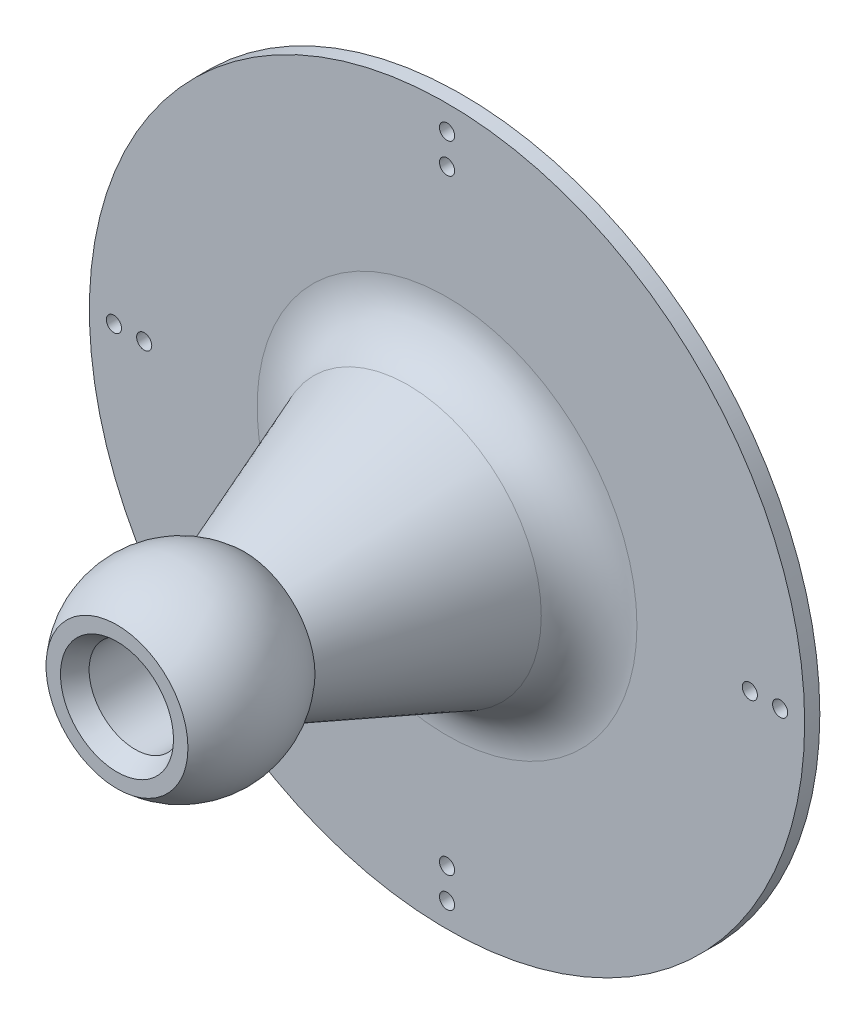
SolidWorks part; units mm, degrees
ref_plane "Front Plane" through (0, 0, 0) normal (0, 0, 1) x (1, 0, 0)
ref_plane "Top Plane" through (0, 0, 0) normal (0, 1, 0) x (1, 0, 0)
ref_plane "Right Plane" through (0, 0, 0) normal (1, 0, 0) x (0, 0, -1)
sketch "Sketch1" plane through (0, 0, 0) normal (0, 1, 0) x (1, 0, 0)
  line L0 (75, 1.2937) -> (0, 1.2937)
  line L1 (0, 1.2937) -> (0, -2.6069)
  line L2 (0, -2.6069) -> (20.0223, -2.6069)
  line L3 (9.652, -22.7279) -> (9.652, -71.088)
  line L4 (9.652, -71.088) -> (14.8807, -71.088)
  line L5 (14.8807, -44.45) -> (31.0649, -1.8813)
  line L6 (31.0649, -1.8813) -> (75, -1.8813)
  line L7 (75, -1.8813) -> (75, 1.2937)
  line L8 (0, 1.2937) -> (0, -71.088) construction
  arc A0 (20.0223, -2.6069) -> (9.652, -22.7279) centre (0, -5.0204) cw
  arc A1 (14.8807, -71.088) -> (14.8807, -44.45) centre (0, -57.769) ccw
revolve "Revolve1" add sketch "Sketch1" angle 360 about L8
sketch "Sketch2" plane through (0, 0, -1.2937) normal (0, 0, -1) x (-1, 0, 0)
  circle A0 centre (0, 0) radius 28.5335
extrude "Cut-Extrude1" cut sketch "Sketch2" against normal blind 3.9006 draft 65.378
hole_wizard "Hole1" positions "Sketch4" profile "Sketch3" legacy
sketch "Sketch4" plane through (0, 0, -1.2937) normal (0, 0, -1) x (-1, 0, 0)
  point P0 (-63.5, 0)
  point P1 (-69.85, 0)
  point P2 (0, 63.5)
  point P3 (0, 69.85)
  point P4 (63.5, 0)
  point P5 (69.85, 0)
  point P6 (0, -63.5)
  point P7 (0, -69.85)
sketch "Sketch3" plane through (63.5, 0, -1.2937) normal (1, 0, 0) x (0, 1, 0)
  line L0 (0, 0) -> (0, 72.3817)
  line L1 (0, 72.3817) -> (1.5875, 72.3817)
  line L2 (1.5875, 72.3817) -> (1.5875, 0)
  line L3 (1.5875, 0) -> (0, 0)
  line L4 (0, 110) -> (0, -10) construction
  dimension "Diameter" = 3.175
  dimension "Depth" = 72.3817
chamfer "Chamfer1" distance 2.1997 angle 60 1 edges at (9.652, 0, 71.088)
fillet "Fillet1" radius 12.7 2 edges at (28.5335, 0, -1.2937) (31.0649, 0, 1.8813)
